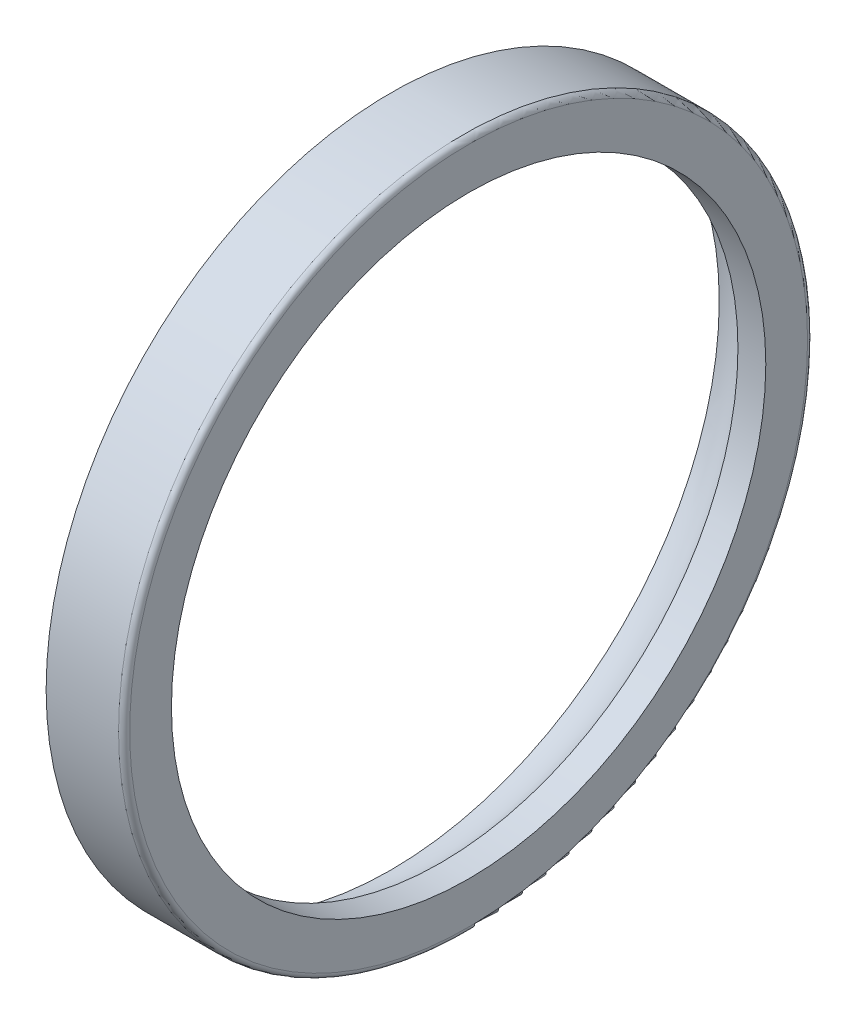
SolidWorks part; units mm, degrees
ref_plane "Plan1" through (0, 0, 0) normal (0, 0, 1) x (1, 0, 0)
ref_plane "Plan2" through (0, 0, 0) normal (0, 1, 0) x (1, 0, 0)
ref_plane "Plan3" through (0, 0, 0) normal (1, 0, 0) x (0, 0, -1)
sketch "Esquisse1" plane through (0, 0, 0) normal (0, 0, 1) x (1, 0, 0)
  line L0 (11.7916, 30.9292) -> (18.2916, 30.9292)
  line L1 (18.7916, 30.4292) -> (18.7916, 26.6792)
  line L2 (18.7916, 26.6792) -> (16.2918, 26.6792)
  line L3 (11.7916, 30.9292) -> (11.7916, 29.5)
  line L5 (11.7916, 32.288) -> (11.7916, 17.4195) construction
  line L6 (43.7916, 0) -> (-206.2084, 0) construction
  line L7 (21.3392, 0) -> (10.2818, 0) construction
  arc A0 (16.2918, 26.6792) -> (11.7916, 29.5) centre (11.7916, 24.5) ccw
  arc A1 (18.2916, 30.9292) -> (18.7916, 30.4292) centre (18.2916, 30.4292) cw
  dimension "D1" = 24.5
  dimension "D2" = 0.5
revolve "Base-Révolution" add sketch "Esquisse1" angle 360 about L7
